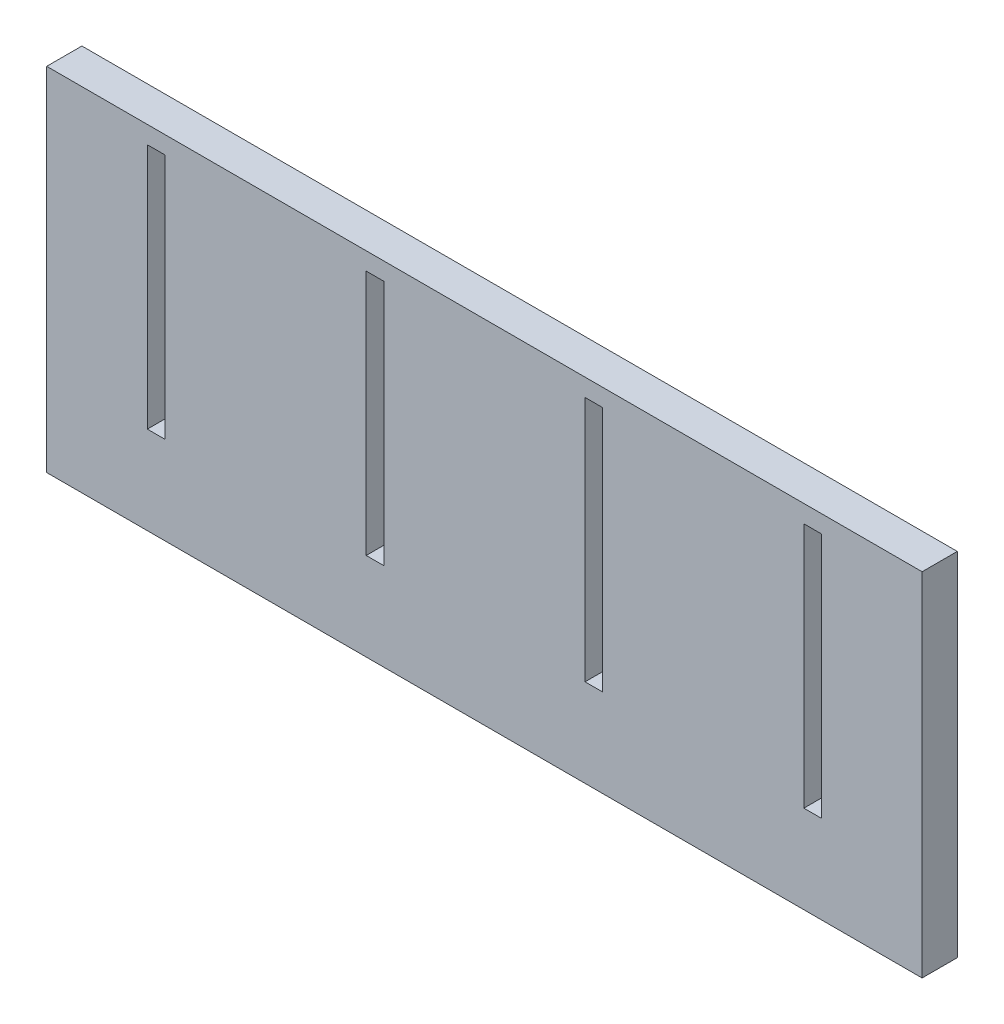
SolidWorks part; units mm, degrees
ref_plane "Front Plane" through (0, 0, 0) normal (0, 0, 1) x (1, 0, 0)
ref_plane "Top Plane" through (0, 0, 0) normal (0, 1, 0) x (1, 0, 0)
ref_plane "Right Plane" through (0, 0, 0) normal (1, 0, 0) x (0, 0, -1)
sketch "Sketch1" plane through (0, 0, 0) normal (0, 0, 1) x (1, 0, 0)
  line L0 (-124.393, -115.7839) -> (0, -115.7839)
  line L1 (-124.393, -115.7839) -> (-124.393, -15.7839)
  line L2 (-124.393, -15.7839) -> (-0.0505, -15.7839)
  line L4 (-33.593, -90.7839) -> (-28.593, -90.7839)
  line L5 (-33.593, -90.7839) -> (-33.593, -20.7839)
  line L6 (-33.593, -20.7839) -> (-28.593, -20.7839)
  line L7 (-28.593, -90.7839) -> (-28.593, -20.7839)
  line L8 (-90.793, -20.7839) -> (-95.793, -20.7839)
  line L9 (-90.793, -20.7839) -> (-90.793, -90.7839)
  line L10 (-90.793, -90.7839) -> (-95.793, -90.7839)
  line L11 (-95.793, -20.7839) -> (-95.793, -90.7839)
  line L12 (28.607, -20.7839) -> (28.607, -90.7839)
  line L13 (90.807, -20.7839) -> (95.807, -20.7839)
  line L14 (0, -115.7839) -> (124.407, -115.7839)
  line L15 (33.607, -20.7839) -> (33.607, -90.7839)
  line L17 (90.807, -90.7839) -> (90.807, -20.7839)
  line L18 (33.607, -20.7839) -> (28.607, -20.7839)
  line L19 (90.807, -90.7839) -> (95.807, -90.7839)
  line L20 (-0.0505, -15.7839) -> (124.407, -15.7839)
  line L21 (124.407, -115.7839) -> (124.407, -15.7839)
  line L22 (95.807, -90.7839) -> (95.807, -20.7839)
  line L23 (33.607, -90.7839) -> (28.607, -90.7839)
  line L24 (124.407, -20.7839) -> (-124.393, -20.7839) construction
  line L25 (124.407, -90.7839) -> (-124.393, -90.7839) construction
  dimension "D1" = 70
  dimension "D2" = 57.2
  dimension "D3" = 57.2
  dimension "D4" = 57.2
  dimension "D5" = 25
  dimension "D6" = 5
  dimension "D7" = 28.6
  dimension "D8" = 28.6
  dimension "D9" = 5
  dimension "D10" = 5
  dimension "D11" = 5
  dimension "D12" = 5
  dimension "D13" = 248.8
extrude "Boss-Extrude1" add sketch "Sketch1" along normal blind 10
